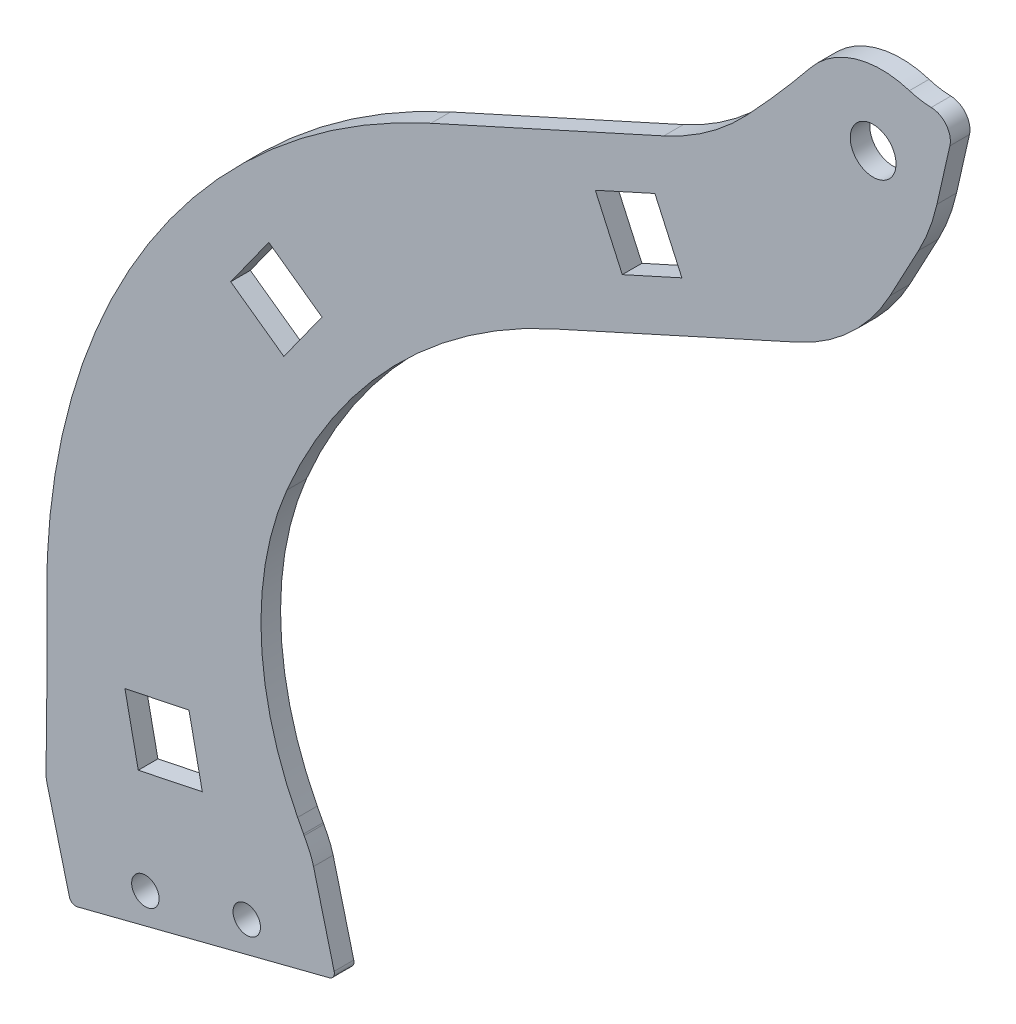
SolidWorks part; units mm, degrees
material "6061 合金"
ref_plane "前视基准面" through (0, 0, 0) normal (0, 0, 1) x (1, 0, 0)
ref_plane "上视基准面" through (0, 0, 0) normal (0, 1, 0) x (1, 0, 0)
ref_plane "右视基准面" through (0, 0, 0) normal (1, 0, 0) x (0, 0, -1)
other "Configuration Table"
sketch "草图1" plane through (0, 0, 0) normal (0, 0, 1) x (1, 0, 0)
  line L0 (-74.3846, 0) -> (17.4339, 0) construction
  line L1 (0, 31.8895) -> (0, -25.7876) construction
  line L11 (-56.839, -53.9876) -> (-54.7995, -63.7774)
  line L12 (-54.7995, -63.7774) -> (-45.0097, -61.7378)
  line L13 (-45.0097, -61.7378) -> (-47.0492, -51.948)
  line L14 (-47.0492, -51.948) -> (-56.839, -53.9876)
  line L15 (-40.671, 7.9535) -> (-32.5433, 2.1277)
  line L16 (-32.5433, 2.1277) -> (-26.7174, 10.2554)
  line L17 (-26.7174, 10.2554) -> (-34.8451, 16.0812)
  line L18 (-34.8451, 16.0812) -> (-40.671, 7.9535)
  line L19 (15.067, 47.9359) -> (19.1928, 38.8267)
  line L20 (19.1928, 38.8267) -> (28.302, 42.9526)
  line L21 (28.302, 42.9526) -> (24.1761, 52.0618)
  line L22 (24.1761, 52.0618) -> (15.067, 47.9359)
  line L23 (60.1085, 56.4801) -> (64.4873, 64.6697)
  line L24 (67.2899, 72.1857) -> (69.2667, 80.9105)
  line L25 (38.5594, 69.8107) -> (38.2224, 69.451)
  line L26 (25.5349, 60.3618) -> (-10.0534, 44.2425)
  line L27 (-68.7626, -58.7637) -> (-68.9008, -71.2835)
  line L28 (-68.7801, -72.3458) -> (-65.3322, -85.8058)
  line L29 (-64.1041, -86.5235) -> (-25.5886, -76.6577)
  line L30 (-24.8568, -75.4379) -> (-28.0084, -63.1344)
  line L31 (8.5664, 26.329) -> (46.0304, 43.2979)
  circle A15 centre (-53.7128, -79.2165) radius 2.1
  circle A16 centre (-38.2132, -75.2462) radius 2.1
  circle A17 centre (57.5371, 74.3955) radius 3.5
  arc A18 (46.0304, 43.2979) -> (60.1085, 56.4801) centre (33.6527, 70.6254) ccw
  arc A19 (64.4873, 64.6697) -> (67.2899, 72.1857) centre (38.0315, 78.8151) ccw
  arc A20 (69.2667, 80.9105) -> (66.417, 84.5725) centre (66.3409, 81.5734) ccw
  arc A21 (63.0866, 85.1324) -> (66.417, 84.5725) centre (66.7215, 96.5686) ccw
  arc A22 (63.0866, 85.1324) -> (47.9703, 80.606) centre (58.8459, 71.7901) ccw
  arc A23 (38.5594, 69.8107) -> (47.9703, 80.606) centre (-107.3958, 206.548) ccw
  arc A24 (25.5349, 60.3618) -> (38.2224, 69.451) centre (9.0314, 96.7985) ccw
  arc A25 (-10.0534, 44.2425) -> (-68.7832, -48.3491) centre (31.2055, -46.8492) ccw
  arc A26 (-68.7626, -58.7637) -> (-68.7832, -48.3491) centre (-468.7382, -54.3488) ccw
  arc A27 (-29.4354, -59.7581) -> (-29.5302, -59.5793) centre (-91.0559, -92.3183) ccw
  arc A28 (-32.0889, -15.3378) -> (-30.4414, -57.8505) centre (13.9501, -34.8419) ccw
  arc A29 (8.5664, 26.329) -> (-32.0889, -15.3378) centre (41.5735, -46.5443) ccw
  spline S0 degree 3 poles (-68.9008, -71.2835) (-68.9048, -71.6426) (-68.8694, -71.9973) (-68.7801, -72.3458) knots 0 0 0 0 1 1 1 1
  spline S1 degree 3 poles (-65.3322, -85.8058) (-65.2663, -86.0633) (-65.094, -86.2874) (-64.7534, -86.485) (-64.6266, -86.5284) (-64.3653, -86.5641) (-64.2327, -86.5565) (-64.1041, -86.5235) knots 0 0 0 0 0.5 0.5 0.75 0.75 1 1 1 1
  spline S2 degree 3 poles (-25.5886, -76.6577) (-25.46, -76.6247) (-25.3386, -76.5666) (-25.1281, -76.4106) (-25.0373, -76.311) (-24.9018, -76.0864) (-24.8561, -75.9601) (-24.8172, -75.6995) (-24.8238, -75.5666) (-24.8568, -75.4379) knots 0 0 0 0 0.25 0.25 0.5 0.5 0.75 0.75 1 1 1 1
  spline S3 degree 3 poles (-28.0084, -63.1344) (-28.1616, -62.536) (-28.3703, -61.9609) (-28.8679, -60.8447) (-29.149, -60.3003) (-29.4354, -59.7581) knots 0 0 0 0 0.5 0.5 1 1 1 1
  spline S4 degree 3 poles (-29.5302, -59.5793) (-29.8362, -59.0042) (-30.1416, -58.4288) (-30.4414, -57.8505) knots 0 0 0 0 1 1 1 1
extrude "凸台-拉伸2" add sketch "草图1" along normal blind 3
